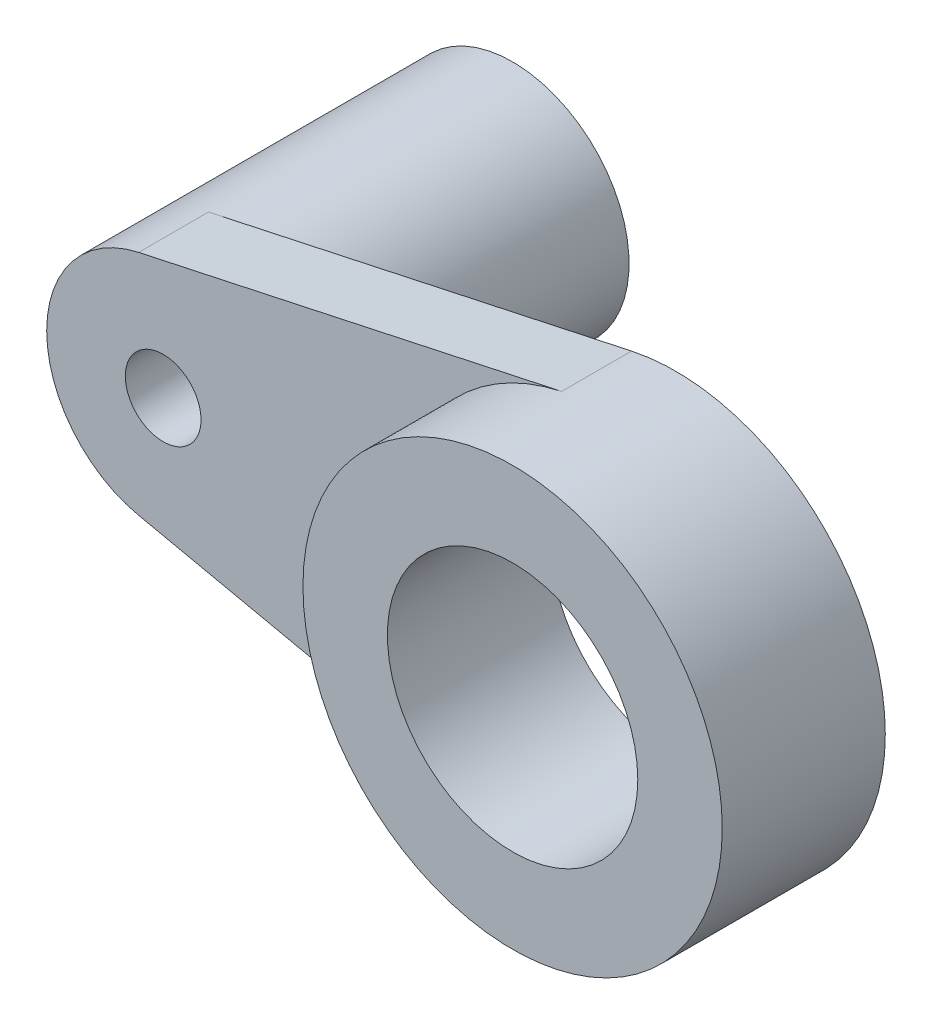
SolidWorks part; units mm, degrees
material "1060 Alloy"
ref_plane "Front Plane" through (0, 0, 0) normal (0, 0, 1) x (1, 0, 0)
ref_plane "Top Plane" through (0, 0, 0) normal (0, 1, 0) x (1, 0, 0)
ref_plane "Right Plane" through (0, 0, 0) normal (1, 0, 0) x (0, 0, -1)
sketch "Sketch1" plane through (0, 0, 0) normal (0, 0, 1) x (1, 0, 0)
  circle A0 centre (0, 0) radius 10.75
  circle A1 centre (0, 0) radius 18
  dimension "D2" = 36
  dimension "D3" = 21.5
extrude "Boss-Extrude1" add sketch "Sketch1" along normal blind 14
sketch "Sketch2" plane through (0, 0, 0) normal (0, 0, -1) x (-1, 0, 0)
  line L0 (40.1053, 9.7759) -> (3.7895, 17.5966)
  line L1 (3.7895, -17.5966) -> (40.1053, -9.7759)
  circle A0 centre (38, 0) radius 3.25
  arc A1 (40.1053, -9.7759) -> (40.1053, 9.7759) centre (38, 0) ccw
  circle A2 centre (0, 0) radius 18 construction
  circle M6 centre (0, 0) radius 18
  dimension "D1" = 6.5
  dimension "D2" = 20
  dimension "D3" = 38
extrude "Boss-Extrude2" add sketch "Sketch2" against normal blind 6 contours L1 A1 L0 A0 M6
sketch "Sketch3" plane through (0, 0, 0) normal (0, 0, -1) x (-1, 0, 0)
  circle A0 centre (38, 0) radius 10
  circle A1 centre (38, 0) radius 3.25
  dimension "D1" = 20
  dimension "D2" = 6.5
extrude "Boss-Extrude3" add sketch "Sketch3" along normal blind 24 contours A0 | A1
